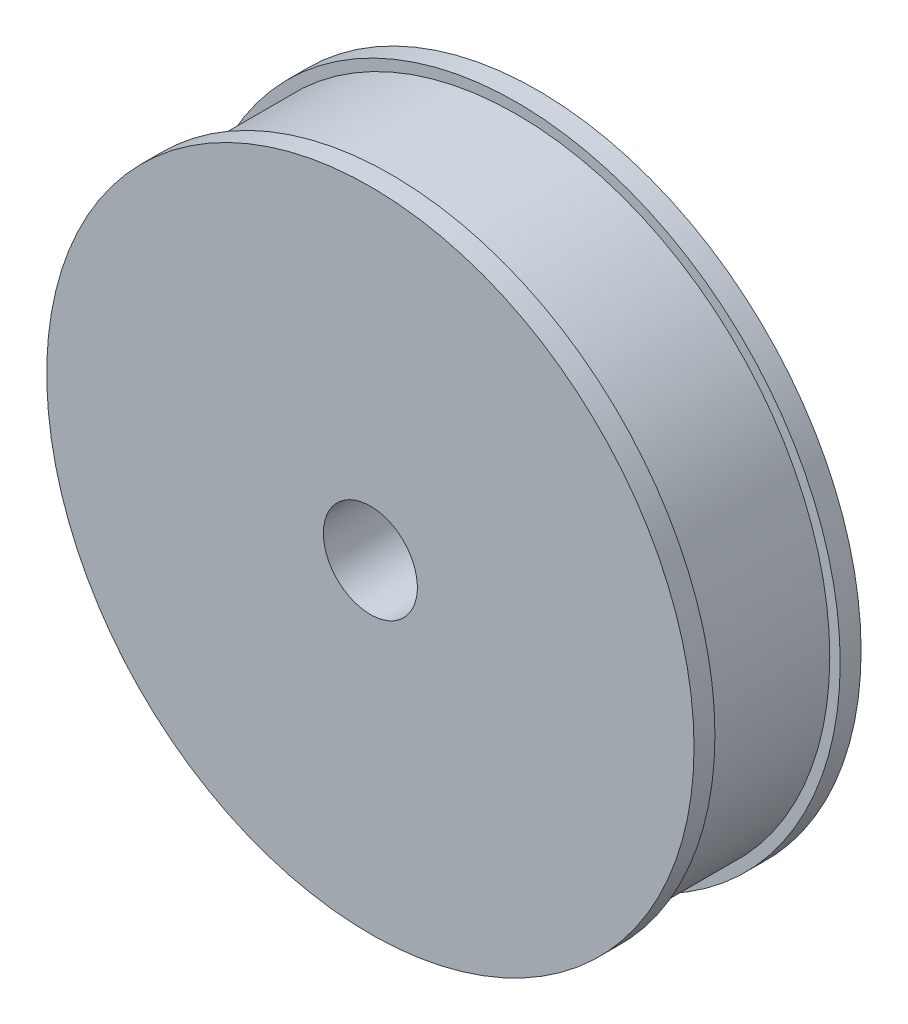
SolidWorks part; units mm, degrees
ref_plane "前视基准面" through (0, 0, 0) normal (0, 0, 1) x (1, 0, 0)
ref_plane "上视基准面" through (0, 0, 0) normal (0, 1, 0) x (1, 0, 0)
ref_plane "右视基准面" through (0, 0, 0) normal (1, 0, 0) x (0, 0, -1)
sketch "草图1" plane through (0, 0, 0) normal (0, 0, 1) x (1, 0, 0)
  circle A0 centre (0, 0) radius 31
  dimension "D1" = 62
extrude "拉伸1" add sketch "草图1" along normal blind 2
sketch "草图2" plane through (0, 0, 2) normal (0, 0, 1) x (1, 0, 0)
  circle A0 centre (0, 0) radius 30
  dimension "D1" = 60
extrude "拉伸2" add sketch "草图2" along normal blind 12
sketch "草图3" plane through (0, 0, 14) normal (0, 0, 1) x (1, 0, 0)
  circle A0 centre (0, 0) radius 31
  dimension "D1" = 62
extrude "拉伸3" add sketch "草图3" along normal blind 2
sketch "草图4" plane through (0, 0, 0) normal (0, 0, -1) x (-1, 0, 0)
  circle A0 centre (0, 0) radius 4.5
  dimension "D1" = 9
extrude "切除-拉伸1" cut sketch "草图4" against normal through all
